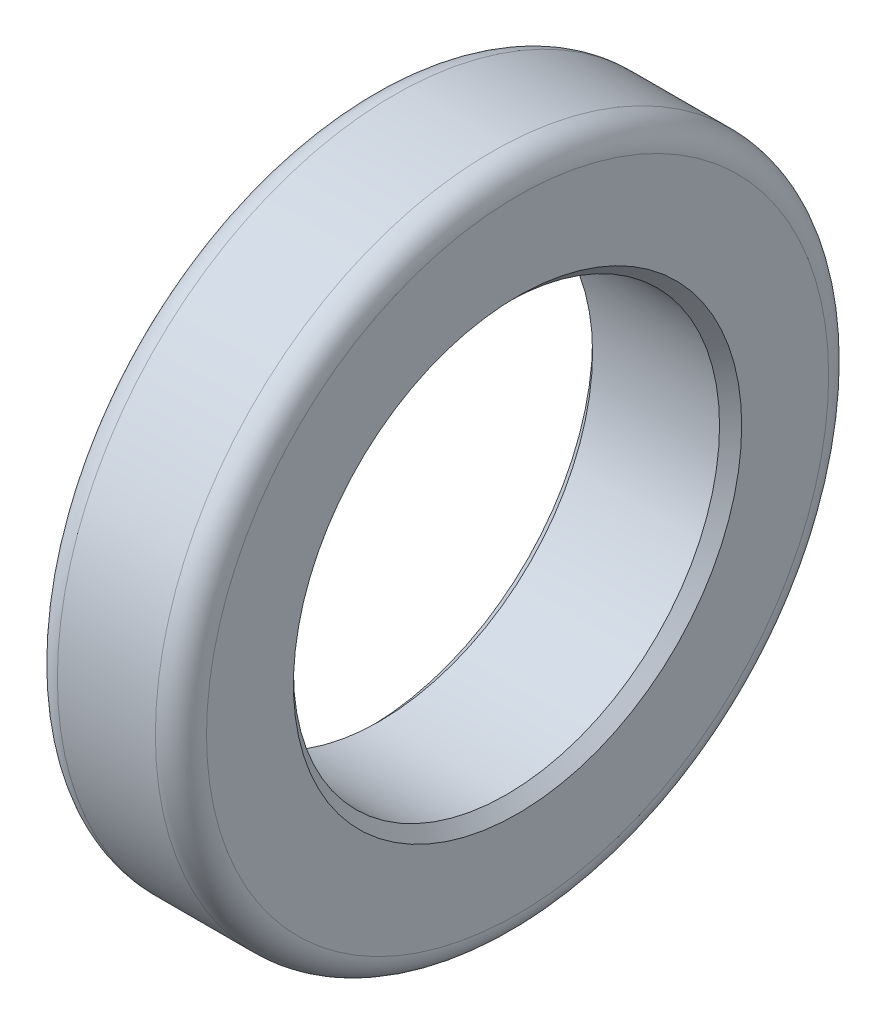
SolidWorks part; units mm, degrees
ref_plane "Front Plane" through (0, 0, 0) normal (0, 0, 1) x (1, 0, 0)
ref_plane "Top Plane" through (0, 0, 0) normal (0, 1, 0) x (1, 0, 0)
ref_plane "Right Plane" through (0, 0, 0) normal (1, 0, 0) x (0, 0, -1)
sketch "Sketch1" plane through (0, 0, 0) normal (1, 0, 0) x (0, 0, -1)
  circle A0 centre (0, 0) radius 39.5
  circle A1 centre (0, 0) radius 25
  dimension "D1" = 79
  dimension "D2" = 50
extrude "Boss-Extrude1" add sketch "Sketch1" along normal mid plane 17.5
fillet "Fillet1" radius 3 2 edges at (8.75, 0, -39.5) (-8.75, 0, -39.5)
chamfer "Chamfer1" distance 1.3 angle 45 2 edges at (-8.75, 0, -25) (8.75, 0, -25)
